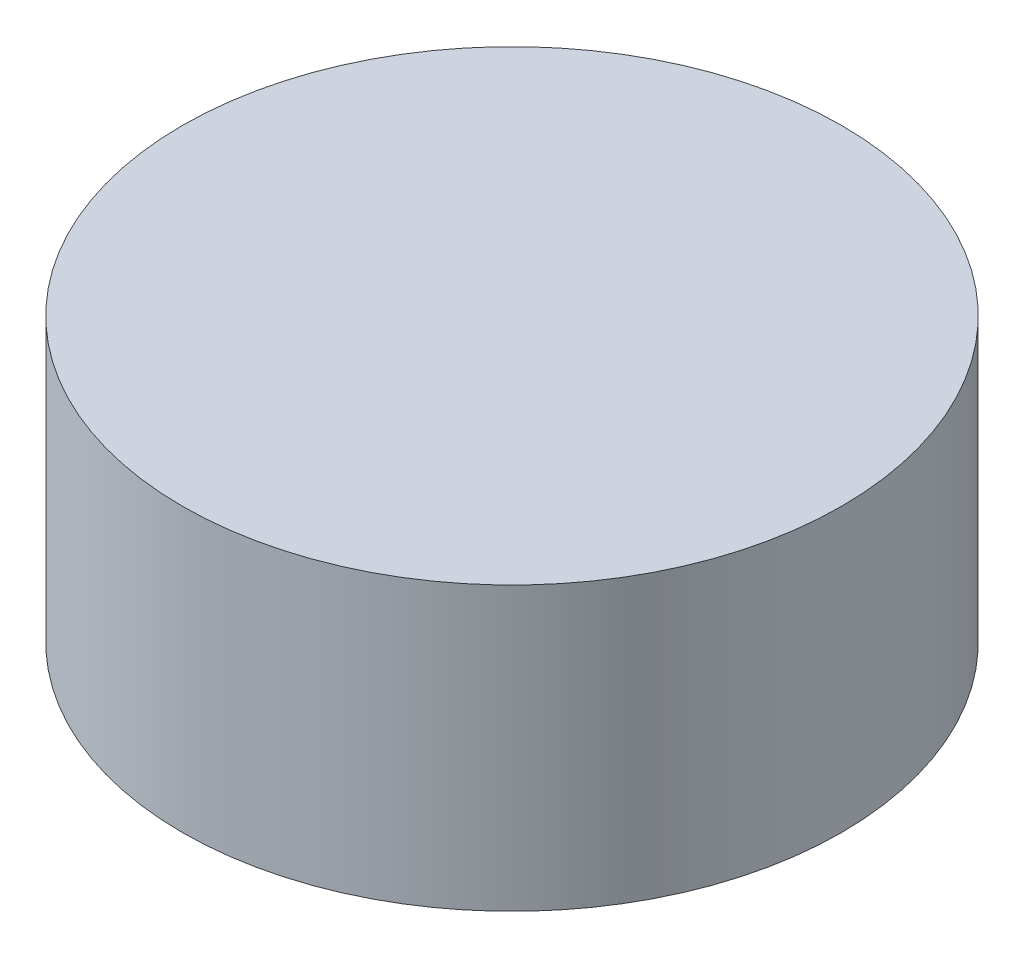
SolidWorks part; units mm, degrees
ref_plane "Front Plane" through (0, 0, 0) normal (0, 0, 1) x (1, 0, 0)
ref_plane "Top Plane" through (0, 0, 0) normal (0, 1, 0) x (1, 0, 0)
ref_plane "Right Plane" through (0, 0, 0) normal (1, 0, 0) x (0, 0, -1)
sketch "Sketch1" plane through (0, 0, 0) normal (0, 1, 0) x (1, 0, 0)
  circle A0 centre (0, 0) radius 17.5
  dimension "D1" = 35
extrude "Boss-Extrude1" add sketch "Sketch1" along normal mid plane 15
